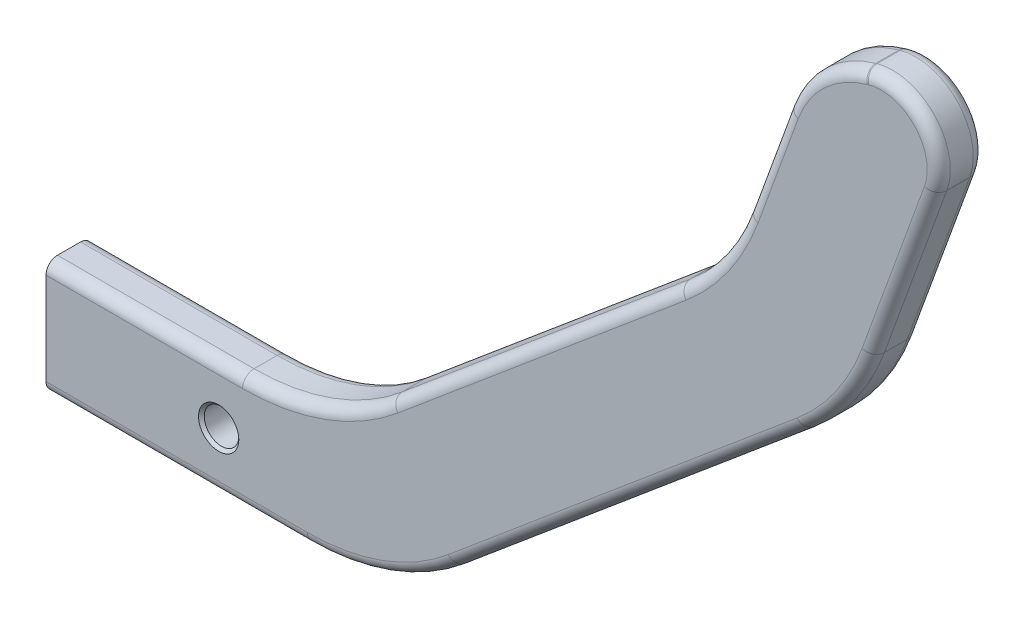
SolidWorks part; units mm, degrees
ref_plane "Piano frontale" through (0, 0, 0) normal (0, 0, 1) x (1, 0, 0)
ref_plane "Piano superiore" through (0, 0, 0) normal (0, 1, 0) x (1, 0, 0)
ref_plane "Piano destro" through (0, 0, 0) normal (1, 0, 0) x (0, 0, -1)
sketch "Schizzo1" plane through (0, 0, 0) normal (0, 0, 1) x (1, 0, 0)
  line L0 (0, 0) -> (22.7206, 0)
  line L1 (35.5763, 4.6791) -> (65.8948, 30.1193)
  line L2 (71.8329, 38.5998) -> (77.252, 53.4888)
  line L4 (64.4028, 53.7755) -> (60.9063, 44.1689)
  line L5 (54.9682, 35.6884) -> (29.9303, 14.6791)
  line L6 (17.0746, 10) -> (0, 10)
  line L7 (0, 10) -> (0, 0)
  line L8 (0, 5) -> (15, 5) construction
  line L9 (71.084, 59.9795) -> (71.1957, 60.011)
  circle A6 centre (15, 5) radius 1.5
  arc A7 (65.8948, 30.1193) -> (71.8329, 38.5998) centre (53.039, 45.4402) ccw
  arc A8 (22.7206, 0) -> (35.5763, 4.6791) centre (22.7206, 20) ccw
  arc A9 (29.9303, 14.6791) -> (17.0746, 10) centre (17.0746, 30) cw
  arc A10 (60.9063, 44.1689) -> (54.9682, 35.6884) centre (42.1124, 51.0093) cw
  arc A11 (71.084, 59.9795) -> (64.4028, 53.7755) centre (73.7997, 50.3553) ccw
  arc A12 (77.252, 53.4888) -> (71.1957, 60.011) centre (72.5536, 55.1989) ccw
  point P1 (30, 10)
  point P3 (85.4828, 49.911)
  point P11 (70, 33.564)
  point P14 (30, 0)
  point P21 (92.752, 53.8506)
  point P24 (66.1546, 58.5885)
  point P30 (80.5909, 62.6621)
  dimension "D10" = 20
  dimension "D11" = 20
  dimension "D12" = 20
  dimension "D13" = 20
  dimension "D14" = 10
  dimension "D3" = 15
  dimension "D15" = 3
  dimension "D16" = 5
  dimension "D1" = 30
  dimension "D2" = 40
  dimension "D4" = 10
  dimension "D5" = 15
  dimension "D6" = 40
  dimension "D7" = 30
  dimension "D8" = 40
  dimension "D9" = 30
extrude "Estrusione-Estrusione1" add sketch "Schizzo1" against normal blind 4
chamfer "Smusso1" distance 0.25 angle 45 2 edges at (16.5, 5, -4) (16.5, 5, 0)
fillet "Raccordo4" radius 1 13 edges at (74.5425, 46.0443, -4) (76.2175, 58.6012, -4) (71.1398, 59.9952, -4) (66.9952, 57.6832, -4) (62.6545, 48.9722, -4) (58.4955, 39.5377, -4) (42.4492, 25.1837, -4) (23.915, 11.2061, -4) (8.5373, 10, -4) (11.3603, 0, -4) (29.561, 1.2061, -4) (50.7356, 17.3992, -4) (69.4221, 33.9687, -4)
fillet "Raccordo5" radius 1 13 edges at (69.4221, 33.9687, 0) (50.7356, 17.3992, 0) (29.561, 1.2061, 0) (11.3603, 0, 0) (8.5373, 10, 0) (23.915, 11.2061, 0) (42.4492, 25.1837, 0) (58.4955, 39.5377, 0) (62.6545, 48.9722, 0) (66.9952, 57.6832, 0) (71.1398, 59.9952, 0) (76.2175, 58.6012, 0) (74.5425, 46.0443, 0)
